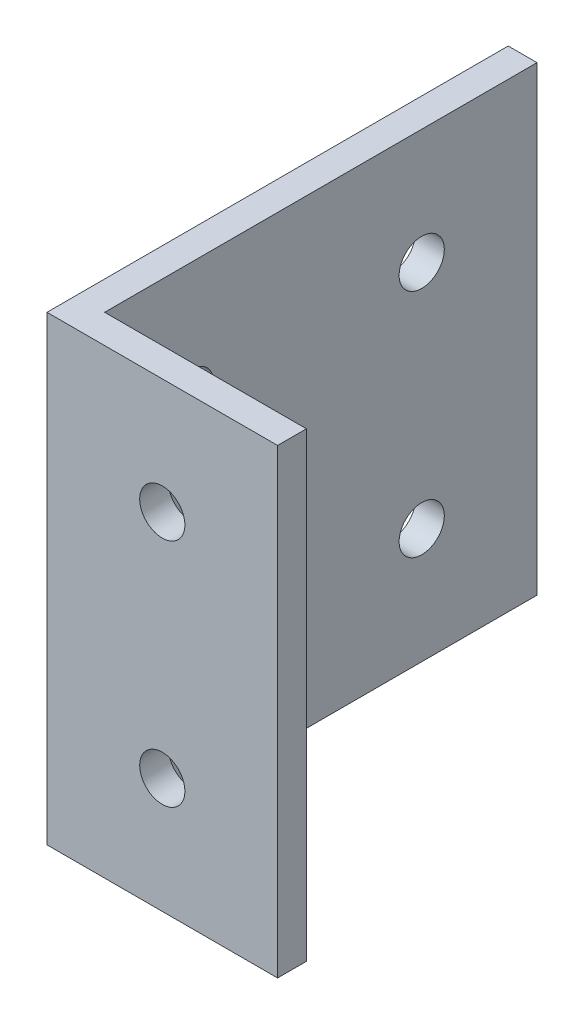
SolidWorks part; units mm, degrees
material "6061-T6 (SS)"
ref_plane "Front Plane" through (0, 0, 0) normal (0, 0, 1) x (1, 0, 0)
ref_plane "Top Plane" through (0, 0, 0) normal (0, 1, 0) x (1, 0, 0)
ref_plane "Right Plane" through (0, 0, 0) normal (1, 0, 0) x (0, 0, -1)
sketch "Sketch1" plane through (0, 0, 0) normal (0, 1, 0) x (1, 0, 0)
  line L0 (0, 0) -> (0, 50.8)
  line L1 (0, 50.8) -> (3.175, 50.8)
  line L2 (3.175, 50.8) -> (3.175, 3.175)
  line L3 (3.175, 3.175) -> (25.4, 3.175)
  line L4 (25.4, 3.175) -> (25.4, 0)
  line L5 (25.4, 0) -> (0, 0)
  dimension "D1" = 3.175
  dimension "D2" = 50.8
  dimension "D3" = 25.4
extrude "Boss-Extrude1" add sketch "Sketch1" along normal blind 50.8
sketch "Sketch2" plane through (3.175, 0, 0) normal (1, 0, 0) x (0, 0, -1)
  line L0 (50.8, 50.8) -> (50.8, 0) construction
  line L1 (3.175, 50.8) -> (50.8, 50.8) construction
  circle A0 centre (38.1, 38.1) radius 2.4892
  circle A1 centre (38.1, 12.7) radius 2.4892
  circle A2 centre (12.7, 12.7) radius 2.4892
  circle A3 centre (12.7, 38.1) radius 2.4892
  dimension "D1" = 4.9784
  dimension "D2" = 12.7
  dimension "D3" = 12.7
  dimension "D4" = 25.4
  dimension "D5" = 25.4
extrude "Cut-Extrude1" cut sketch "Sketch2" against normal through all
sketch "Sketch3" plane through (0, 0, -3.175) normal (0, 0, -1) x (-1, 0, 0)
  line L2 (-25.4, 0) -> (-3.175, 0) construction
  line L3 (-25.4, 50.8) -> (-25.4, 0) construction
  circle A0 centre (-12.7, 38.1) radius 2.4892
  circle A1 centre (-12.7, 12.7) radius 2.4892
  point P8 (0, 0)
  dimension "D1" = 4.9784
  dimension "D2" = 25.4
  dimension "D3" = 12.7
  dimension "D4" = 12.7
extrude "Cut-Extrude2" cut sketch "Sketch3" against normal through all
